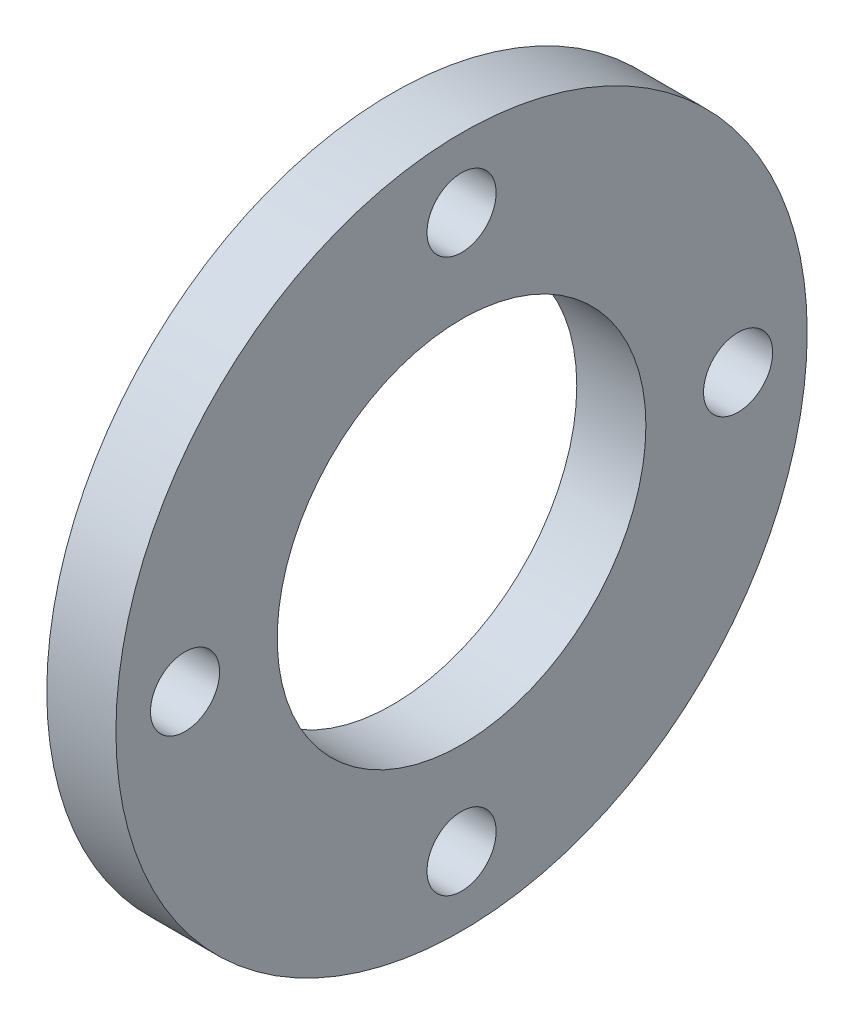
SolidWorks part; units mm, degrees
ref_plane "Front Plane" through (0, 0, 0) normal (0, 0, 1) x (1, 0, 0)
ref_plane "Top Plane" through (0, 0, 0) normal (0, 1, 0) x (1, 0, 0)
ref_plane "Right Plane" through (0, 0, 0) normal (1, 0, 0) x (0, 0, -1)
sketch "Sketch1" plane through (0, 0, 0) normal (1, 0, 0) x (0, 0, -1)
  line L0 (0, 0) -> (0, 12) construction
  circle A0 centre (0, 0) radius 15
  circle A1 centre (0, 0) radius 8
  circle A2 centre (0, 12) radius 1.5
  circle A3 centre (12, 0) radius 1.5
  circle A4 centre (0, -12) radius 1.5
  circle A5 centre (-12, 0) radius 1.5
  point P14 (0, 0)
  dimension "D2" = 3
  dimension "D3" = 16
  dimension "D4" = 30
  dimension "D1" = 12
  dimension "D6" = 12
  dimension "D7" = 12
  dimension "D5" = 4
extrude "Boss-Extrude1" add sketch "Sketch1" along normal blind 3
